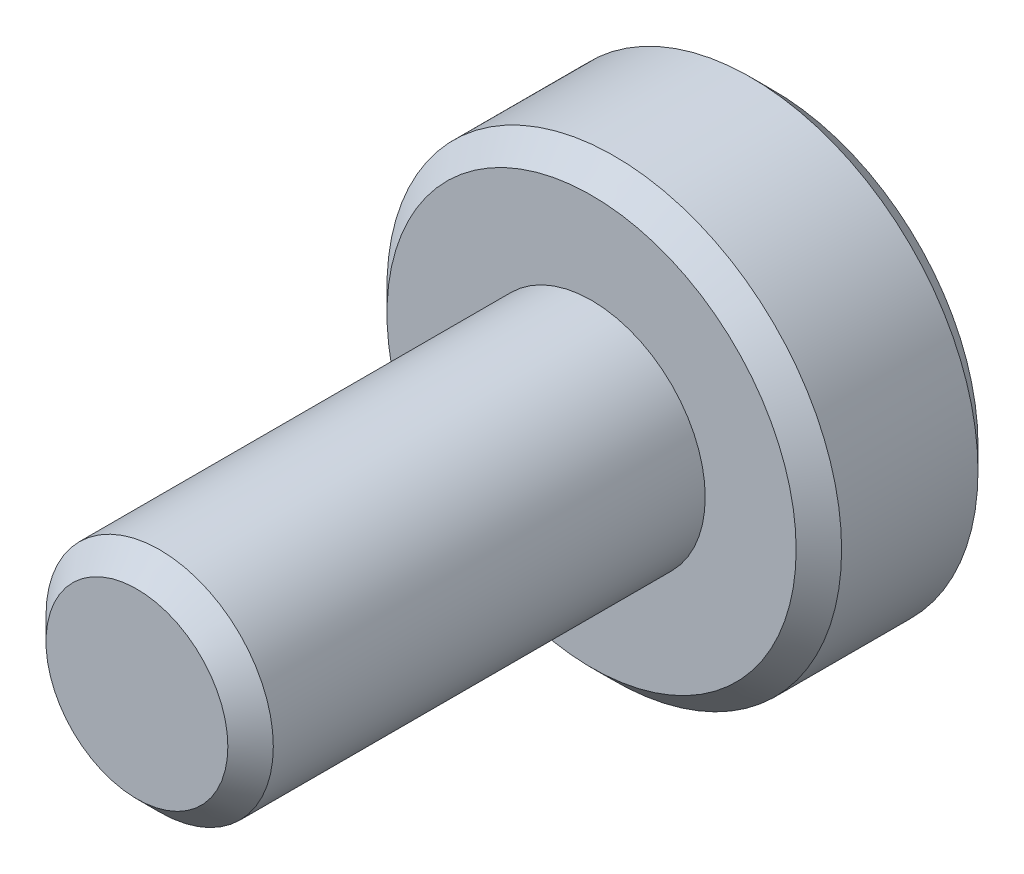
SolidWorks part; units mm, degrees
ref_plane "Alzado" through (0, 0, 0) normal (0, 0, 1) x (1, 0, 0)
ref_plane "Planta" through (0, 0, 0) normal (0, 1, 0) x (1, 0, 0)
ref_plane "Vista lateral" through (0, 0, 0) normal (1, 0, 0) x (0, 0, -1)
sketch "Croquis1" plane through (0, 0, 0) normal (0, 0, 1) x (1, 0, 0)
  circle A0 centre (0, 0) radius 10
  dimension "D1" = 20
extrude "Saliente-Extruir1" add sketch "Croquis1" along normal blind 8
sketch "Croquis2" plane through (0, 0, 8) normal (0, 0, 1) x (1, 0, 0)
  circle A0 centre (0, 0) radius 5
  dimension "D1" = 10
extrude "Saliente-Extruir2" add sketch "Croquis2" along normal blind 20
chamfer "Chaflán1" distance 1 angle 45 2 edges at (10, 0, 0) (10, 0, 8)
chamfer "Chaflán2" distance 1 angle 45 1 edges at (5, 0, 28)
